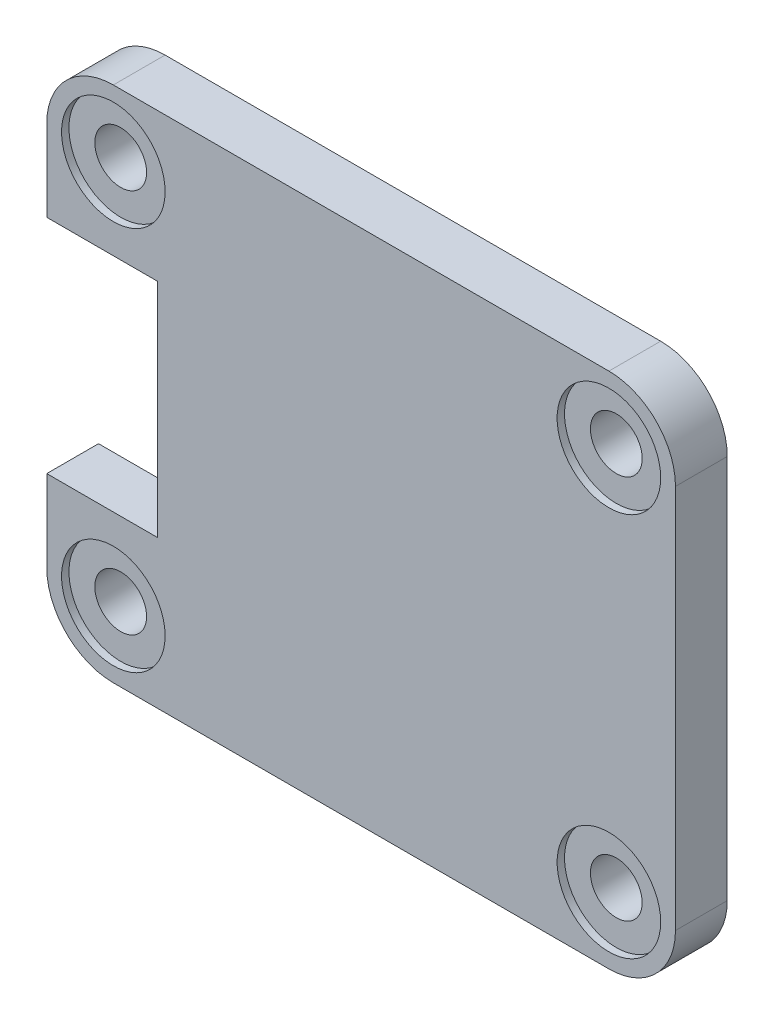
SolidWorks part; units mm, degrees
ref_plane "Front Plane" through (0, 0, 0) normal (0, 0, 1) x (1, 0, 0)
ref_plane "Top Plane" through (0, 0, 0) normal (0, 1, 0) x (1, 0, 0)
ref_plane "Right Plane" through (0, 0, 0) normal (1, 0, 0) x (0, 0, -1)
sketch "Sketch9" plane through (0, 0, 0) normal (0, 0, 1) x (1, 0, 0)
  line L1 (-67, 70) -> (67, 70)
  line L2 (-85, 52) -> (-85, -52)
  line L3 (-67, -70) -> (67, -70)
  line L4 (85, 52) -> (85, -52)
  arc A0 (-67, 70) -> (-85, 52) centre (-67, 52) ccw
  arc A1 (-67, -70) -> (-85, -52) centre (-67, -52) cw
  arc A2 (67, -70) -> (85, -52) centre (67, -52) ccw
  arc A3 (67, 70) -> (85, 52) centre (67, 52) cw
  point P0 (0, 0)
  point P8 (-85, 70)
  dimension "D5" = 18
  dimension "D1" = 85
  dimension "D2" = 70
  dimension "D3" = 85
  dimension "D4" = 70
extrude "Boss-Extrude1" add sketch "Sketch9" against normal blind 14 contours A0 L2 A1 L3 A2 L4 A3 L1
sketch "Sketch10" plane through (0, 0, 0) normal (0, 0, 1) x (1, 0, 0)
  line L0 (-85, 52) -> (-85, -52) construction
  line L2 (-67, 70) -> (67, 70) construction
  circle A0 centre (67, 52) radius 14
  circle A1 centre (67, 52) radius 7
  circle A2 centre (-67, 52) radius 7
  circle A3 centre (-67, 52) radius 14
  circle A4 centre (67, -52) radius 7
  circle A5 centre (67, -52) radius 14
  circle A6 centre (-67, -52) radius 14
  circle A7 centre (-67, -52) radius 7
  dimension "D1" = 28
  dimension "D2" = 14
  dimension "D8" = 14
  dimension "D9" = 28
  dimension "D10" = 14
  dimension "D11" = 28
  dimension "D12" = 14
  dimension "D13" = 28
  dimension "D3" = 104
  dimension "D5" = 52
  dimension "D6" = 67
  dimension "D7" = 134
  dimension "D14" = 18
extrude "Cut-Extrude1" cut sketch "Sketch10" against normal blind 14 contours A1 | A4 | A2 | A7
sketch "Sketch11" plane through (0, 0, 0) normal (0, 0, 1) x (1, 0, 0)
  circle A0 centre (-67, 52) radius 14
  circle A1 centre (67, 52) radius 14
  circle A2 centre (67, -52) radius 14
  circle A3 centre (-67, -52) radius 14
  dimension "D1" = 28
  dimension "D2" = 28
  dimension "D3" = 28
  dimension "D4" = 28
extrude "Cut-Extrude3" cut sketch "Sketch11" against normal blind 2 contours A3 | A2 | A1 | A0
sketch "Sketch12" plane through (0, 0, 0) normal (0, 0, 1) x (1, 0, 0)
  line L0 (-85, 52) -> (-85, -52) construction
  line L1 (-55, 30) -> (-85, 30)
  line L2 (-55, 30) -> (-55, -30)
  line L3 (-55, -30) -> (-85, -30)
  line L4 (-85, 30) -> (-85, -30)
  point P0 (-71.6529, 0)
  dimension "D1" = 0
  dimension "D2" = 30
  dimension "D3" = 60
  dimension "D4" = 30
extrude "Cut-Extrude4" cut sketch "Sketch12" against normal blind 14
